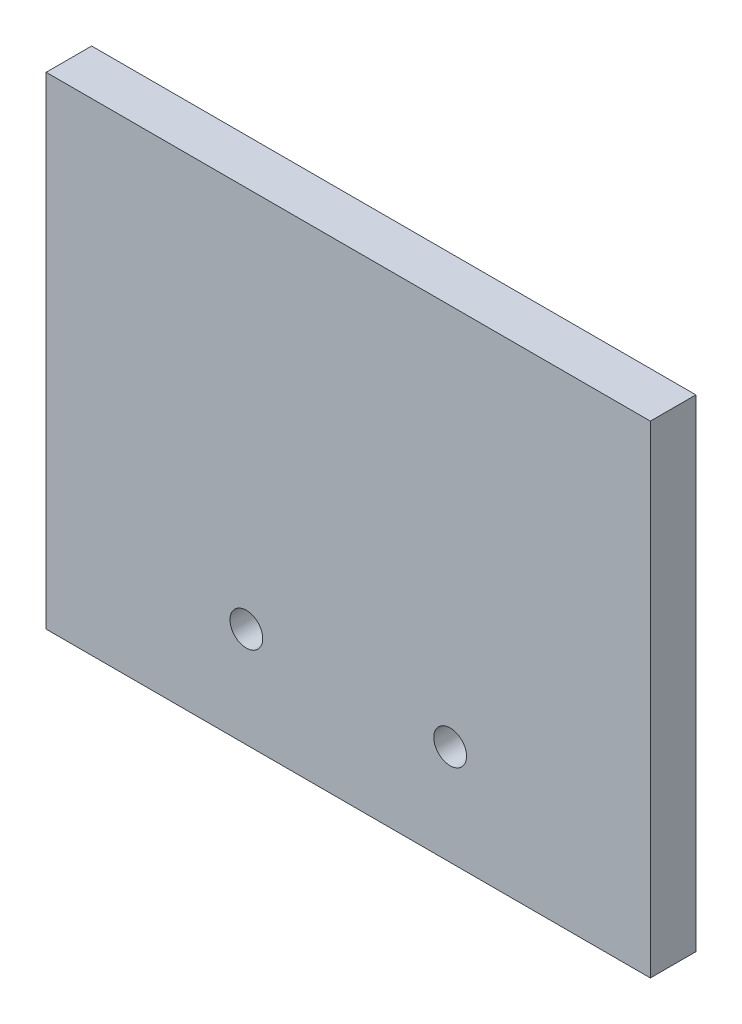
SolidWorks part; units mm, degrees
ref_plane "前视基准面" through (0, 0, 0) normal (0, 0, 1) x (1, 0, 0)
ref_plane "上视基准面" through (0, 0, 0) normal (0, 1, 0) x (1, 0, 0)
ref_plane "右视基准面" through (0, 0, 0) normal (1, 0, 0) x (0, 0, -1)
sketch "Sketch1" plane through (0, 0, 0) normal (0, 1, 0) x (1, 0, 0)
  line L1 (0, 0) -> (50, 0)
  line L2 (0, 0) -> (0, 9.1)
  line L3 (0, 9.1) -> (50, 9.1)
  line L4 (50, 0) -> (50, 9.1)
  dimension "D1" = 50
  dimension "D2" = 9.1
extrude "Boss-Extrude1" add sketch "Sketch1" along normal blind 2
sketch "Sketch2" plane through (0, 2, 0) normal (0, 1, 0) x (1, 0, 0)
  line L0 (50, 9.1) -> (0, 9.1) construction
  line L1 (12.5, 9.1) -> (37.5, 9.1)
  line L2 (12.5, 9.1) -> (12.5, 2.5)
  line L3 (12.5, 2.5) -> (37.5, 2.5)
  line L4 (37.5, 9.1) -> (37.5, 2.5)
  line L5 (0, 9.1) -> (0, 0) construction
  line L6 (50, 0) -> (50, 9.1) construction
  point P8 (50, 4.55)
  dimension "D1" = 6.6
  dimension "D2" = 12.5
  dimension "D3" = 12.5
extrude "Cut-Extrude1" cut sketch "Sketch2" against normal blind 2
sketch "Sketch3" plane through (0, 2, 0) normal (0, 1, 0) x (1, 0, 0)
  line L0 (12.5, 9.1) -> (0, 9.1) construction
  line L1 (50, 9.1) -> (37.5, 9.1) construction
  line L3 (37.5, 2.5) -> (37.5, 9.1) construction
  line L5 (0, 9.1) -> (0, 0) construction
  circle A0 centre (6.25, 5.8) radius 1.8
  circle A1 centre (43.75, 5.8) radius 1.8
  dimension "D1" = 3.6
  dimension "D2" = 3.6
  dimension "D4" = 3.3
  dimension "D3" = 3.3
  dimension "D5" = 6.25
  dimension "D6" = 6.25
extrude "Cut-Extrude2" cut sketch "Sketch3" against normal blind 2
sketch "Sketch4" plane through (0, 2, 0) normal (0, 1, 0) x (1, 0, 0)
  line L0 (0, 0) -> (50, 0) construction
  line L1 (-8.2, 0) -> (58.2, 0)
  line L2 (-8.2, 0) -> (-8.2, -130)
  line L3 (-8.2, -130) -> (58.2, -130)
  line L4 (58.2, 0) -> (58.2, -130)
  line L5 (12.5, 2.5) -> (37.5, 2.5) construction
  point P6 (25, 2.5)
  dimension "D1" = 130
  dimension "D2" = 0
  dimension "D3" = 33.2
  dimension "D4" = 66.4
extrude "Boss-Extrude2" add sketch "Sketch4" against normal blind 2
sketch "Sketch5" plane through (0, 0, 130) normal (0, 0, 1) x (1, 0, 0)
  line L1 (-8.2, 2) -> (58.2, 2)
  line L2 (-8.2, 2) -> (-8.2, 0)
  line L3 (-8.2, 0) -> (58.2, 0)
  line L4 (58.2, 2) -> (58.2, 0)
extrude "Boss-Extrude3" add sketch "Sketch5" along normal blind 2.5
sketch "Sketch6" plane through (0, 2, 0) normal (0, 1, 0) x (1, 0, 0)
  line L1 (-8.2, -132.5) -> (-16.8, -132.5)
  line L2 (-8.2, -132.5) -> (-8.2, -70)
  line L3 (-8.2, -70) -> (-16.8, -70)
  line L4 (-16.8, -132.5) -> (-16.8, -70)
  line L5 (58.2, -132.5) -> (66.8, -132.5)
  line L6 (58.2, -132.5) -> (58.2, -70)
  line L7 (58.2, -70) -> (66.8, -70)
  line L8 (66.8, -132.5) -> (66.8, -70)
  dimension "D1" = 8.6
  dimension "D2" = 8.6
  dimension "D3" = 62.5
  dimension "D4" = 62.5
extrude "Boss-Extrude4" add sketch "Sketch6" against normal blind 2
sketch "Sketch7" plane through (0, 2, 0) normal (0, 1, 0) x (1, 0, 0)
  line L0 (-13.5, -64.2883) -> (-13.5, -157.5169) construction
  line L1 (63.5, -64.2883) -> (63.5, -152.5529) construction
  line L2 (-16.8, -70) -> (-16.8, -132.5) construction
  line L3 (66.8, -132.5) -> (66.8, -70) construction
  line L4 (-8.2, -70) -> (-16.8, -70) construction
  line L5 (66.8, -132.5) -> (-16.8, -132.5) construction
  line L6 (66.8, -70) -> (58.2, -70) construction
  line L7 (-15, -115) -> (-12, -115)
  line L8 (-15, -115) -> (-15, -120)
  line L9 (-15, -120) -> (-12, -120)
  line L10 (-12, -115) -> (-12, -120)
  line L11 (62, -115) -> (65, -115)
  line L12 (62, -115) -> (62, -120)
  line L13 (62, -120) -> (65, -120)
  line L14 (65, -115) -> (65, -120)
  circle A0 centre (-13.5, -77) radius 1.8
  circle A1 centre (-13.5, -101.25) radius 1.8
  circle A2 centre (-13.5, -125.5) radius 1.8
  circle A3 centre (63.5, -77) radius 1.8
  circle A4 centre (63.5, -101.25) radius 1.8
  circle A5 centre (63.5, -125.5) radius 1.8
  dimension "D3" = 3.6
  dimension "D4" = 3.6
  dimension "D6" = 3.6
  dimension "D12" = 3.6
  dimension "D13" = 3.6
  dimension "D14" = 3.6
  dimension "D1" = 3.3
  dimension "D2" = 3.3
  dimension "D5" = 31.25
  dimension "D7" = 7
  dimension "D8" = 1.5
  dimension "D9" = 3
  dimension "D10" = 5
  dimension "D11" = 12.5
  dimension "D15" = 1.5
  dimension "D16" = 3
  dimension "D17" = 7
  dimension "D18" = 7
extrude "Cut-Extrude3" cut sketch "Sketch7" against normal blind 2
sketch "Sketch8" plane through (0, 2, 0) normal (0, 1, 0) x (1, 0, 0)
  line L0 (25, 2.5) -> (25, -143.8166) construction
  line L1 (12.5, 2.5) -> (37.5, 2.5) construction
  line L3 (12.5, 0) -> (37.5, 0)
  line L4 (12.5, 0) -> (12.5, -45)
  line L5 (12.5, -45) -> (37.5, -45)
  line L6 (37.5, 0) -> (37.5, -45)
  dimension "D1" = 25
  dimension "D2" = 12.5
  dimension "D3" = 45
extrude "Cut-Extrude4" cut sketch "Sketch8" against normal blind 20
sketch "Sketch9" plane through (0, 2, 0) normal (0, 1, 0) x (1, 0, 0)
  line L0 (37.5, -45) -> (37.5, 0) construction
  line L1 (12.5, 0) -> (37.5, 0)
  line L2 (12.5, 0) -> (12.5, -10)
  line L3 (12.5, -10) -> (37.5, -10)
  line L4 (37.5, 0) -> (37.5, -10)
  dimension "D1" = 10
extrude "Boss-Extrude5" add sketch "Sketch9" against normal blind 2
sketch "Sketch10" plane through (0, 2, 0) normal (0, 1, 0) x (1, 0, 0)
  line L0 (-8.2, 0) -> (-8.2, -70) construction
  line L1 (-8.2, -16) -> (-42.9, -16)
  line L2 (-8.2, -16) -> (-8.2, -43.07)
  line L3 (-8.2, -43.07) -> (-42.9, -43.07)
  line L4 (-42.9, -16) -> (-42.9, -43.07)
  line L5 (0, 0) -> (-8.2, 0) construction
  line L6 (58.2, -70) -> (58.2, 0) construction
  line L7 (58.2, -16) -> (92.9, -16)
  line L8 (58.2, -16) -> (58.2, -43.07)
  line L9 (58.2, -43.07) -> (92.9, -43.07)
  line L10 (92.9, -16) -> (92.9, -43.07)
  dimension "D1" = 16
  dimension "D2" = 27.07
  dimension "D3" = 34.7
  dimension "D4" = 34.7
extrude "Boss-Extrude6" add sketch "Sketch10" against normal blind 2
sketch "Sketch11" plane through (0, 2, 0) normal (0, 1, 0) x (1, 0, 0)
  line L0 (-48.2559, -39.82) -> (25.7485, -39.82) construction
  line L1 (-47.1851, -19.25) -> (20.7514, -19.25) construction
  line L2 (-8.2, -16) -> (-42.9, -16) construction
  line L3 (-42.9, -43.07) -> (-8.2, -43.07) construction
  line L4 (-42.9, -16) -> (-42.9, -43.07) construction
  circle A0 centre (-36.9, -19.25) radius 1.8
  circle A1 centre (-36.9, -39.82) radius 1.8
  circle A2 centre (-22.6, -19.25) radius 1.8
  circle A3 centre (-22.6, -39.82) radius 1.8
  dimension "D5" = 3.6
  dimension "D6" = 3.6
  dimension "D7" = 3.6
  dimension "D8" = 3.6
  dimension "D10" = 20.3
  dimension "D1" = 3.25
  dimension "D2" = 3.25
  dimension "D3" = 6
  dimension "D4" = 6
  dimension "D9" = 20.3
extrude "Cut-Extrude5" cut sketch "Sketch11" against normal blind 2
sketch "Sketch12" plane through (0, 2, 0) normal (0, 1, 0) x (1, 0, 0)
  line L0 (39.2942, -19.25) -> (115.8735, -19.25) construction
  line L1 (40.8036, -39.82) -> (109.9769, -39.82) construction
  line L2 (92.9, -43.07) -> (92.9, -16) construction
  circle A0 centre (72.6, -19.25) radius 1.8
  circle A1 centre (86.9, -19.25) radius 1.8
  circle A2 centre (72.6, -39.82) radius 1.8
  circle A3 centre (86.9, -39.82) radius 1.8
  dimension "D1" = 3.6
  dimension "D2" = 3.6
  dimension "D5" = 3.6
  dimension "D6" = 3.6
  dimension "D3" = 6
  dimension "D4" = 20.3
extrude "Cut-Extrude6" cut sketch "Sketch12" against normal blind 2
sketch "Sketch13" plane through (-42.9, 0, 0) normal (-1, 0, 0) x (0, 0, 1)
  line L1 (16, 2) -> (14, 2)
  line L2 (16, 2) -> (16, 0)
  line L3 (16, 0) -> (14, 0)
  line L4 (14, 2) -> (14, 0)
  line L5 (43.07, 2) -> (45.07, 2)
  line L6 (43.07, 2) -> (43.07, 0)
  line L7 (43.07, 0) -> (45.07, 0)
  line L8 (45.07, 2) -> (45.07, 0)
  dimension "D1" = 2
  dimension "D2" = 2
extrude "Boss-Extrude7" add sketch "Sketch13" against normal blind 44
sketch "Sketch14" plane through (92.9, 0, 0) normal (1, 0, 0) x (0, 0, -1)
  line L1 (-16, 2) -> (-14, 2)
  line L2 (-16, 2) -> (-16, 0)
  line L3 (-16, 0) -> (-14, 0)
  line L4 (-14, 2) -> (-14, 0)
  line L5 (-43.07, 0) -> (-45.07, 0)
  line L6 (-43.07, 0) -> (-43.07, 2)
  line L7 (-43.07, 2) -> (-45.07, 2)
  line L8 (-45.07, 0) -> (-45.07, 2)
  dimension "D1" = 2
  dimension "D2" = 2
extrude "Boss-Extrude8" add sketch "Sketch14" against normal blind 46
sketch "Sketch16" plane through (0, 2, 0) normal (0, 1, 0) x (1, 0, 0)
  line L0 (66.8, -132.5) -> (-16.8, -132.5) construction
  line L1 (4, -132.5) -> (46, -132.5)
  line L2 (4, -132.5) -> (4, -175.5)
  line L3 (4, -175.5) -> (46, -175.5)
  line L4 (46, -132.5) -> (46, -175.5)
  line L5 (37.5, -45) -> (12.5, -45) construction
  point P6 (25, -45)
  dimension "D1" = 42
  dimension "D2" = 43
  dimension "D3" = 21
extrude "Boss-Extrude10" add sketch "Sketch16" against normal blind 2
sketch "Sketch18" plane through (0, 2, 0) normal (0, 1, 0) x (1, 0, 0)
  line L0 (4, -175.5) -> (46, -175.5) construction
  line L1 (4, -132.5) -> (4, -175.5) construction
  line L2 (46, -175.5) -> (46, -132.5) construction
  line L3 (4, -132.5) -> (-16.8, -132.5) construction
  line L4 (66.8, -132.5) -> (46, -132.5) construction
  circle A0 centre (8.74, -171.03) radius 1.8
  circle A1 centre (41.26, -171.03) radius 1.8
  circle A2 centre (8.74, -138.5) radius 1.8
  circle A3 centre (41.26, -138.5) radius 1.8
  dimension "D3" = 3.6
  dimension "D6" = 3.6
  dimension "D7" = 3.6
  dimension "D8" = 3.6
  dimension "D1" = 4.47
  dimension "D2" = 4.74
  dimension "D4" = 4.47
  dimension "D5" = 4.74
  dimension "D9" = 6
  dimension "D10" = 6
extrude "Cut-Extrude7" cut sketch "Sketch18" against normal blind 2
sketch "Sketch20" plane through (0, 2, 0) normal (0, 1, 0) x (1, 0, 0)
  line L0 (-2, -132.5) -> (4, -132.5)
  line L1 (4, -132.5) -> (-16.8, -132.5) construction
  line L2 (4, -132.5) -> (4, -138.5)
  line L3 (4, -132.5) -> (4, -175.5) construction
  line L4 (46, -138.5) -> (46, -132.5)
  line L5 (46, -175.5) -> (46, -132.5) construction
  line L6 (46, -132.5) -> (52, -132.5)
  line L7 (66.8, -132.5) -> (46, -132.5) construction
  arc A0 (-2, -132.5) -> (4, -138.5) centre (-2, -138.5) cw
  arc A1 (52, -132.5) -> (46, -138.5) centre (52, -138.5) ccw
  dimension "D1" = 6
  dimension "D2" = 6
  dimension "D3" = 6
extrude "Boss-Extrude12" add sketch "Sketch20" against normal blind 2 contours L0 A0 L2 | A1 L6 L4
sketch "Sketch21" plane through (0, 0, -9.1) normal (0, 0, -1) x (-1, 0, 0)
  line L1 (-50, 2) -> (-52, 2)
  line L2 (-50, 2) -> (-50, 0)
  line L3 (-50, 0) -> (-52, 0)
  line L4 (-52, 2) -> (-52, 0)
  line L5 (-37.5, 2) -> (-35.5, 2)
  line L6 (-37.5, 2) -> (-37.5, 0)
  line L7 (-37.5, 0) -> (-35.5, 0)
  line L8 (-35.5, 2) -> (-35.5, 0)
  line L9 (-12.5, 2) -> (-14.5, 2)
  line L10 (-12.5, 2) -> (-12.5, 0)
  line L11 (-12.5, 0) -> (-14.5, 0)
  line L12 (-14.5, 2) -> (-14.5, 0)
  line L13 (0, 2) -> (2, 2)
  line L14 (0, 2) -> (0, 0)
  line L15 (0, 0) -> (2, 0)
  line L16 (2, 2) -> (2, 0)
  dimension "D1" = 2
  dimension "D2" = 2
  dimension "D3" = 2
  dimension "D4" = 2
extrude "Boss-Extrude13" add sketch "Sketch21" against normal blind 10
sketch "Sketch25" plane through (0, 2, 0) normal (0, 1, 0) x (1, 0, 0)
  line L0 (-11.7, -6.4239) -> (-11.7, -56.5762) construction
  line L1 (-8.2, 0) -> (-8.2, -14) construction
  line L2 (61.7, -6.4239) -> (61.7, -56.5762) construction
  line L3 (58.2, -14) -> (58.2, 0) construction
  line L4 (-8.2, -14) -> (-42.9, -14) construction
  line L5 (-13.2, -20) -> (-10.2, -20)
  line L6 (-13.2, -20) -> (-13.2, -25)
  line L7 (-13.2, -25) -> (-10.2, -25)
  line L8 (-10.2, -20) -> (-10.2, -25)
  line L9 (-8.2, -45.07) -> (-42.9, -45.07) construction
  line L10 (-13.2, -34.07) -> (-10.2, -34.07)
  line L11 (-13.2, -34.07) -> (-13.2, -39.07)
  line L12 (-13.2, -39.07) -> (-10.2, -39.07)
  line L13 (-10.2, -34.07) -> (-10.2, -39.07)
  line L14 (58.2, -14) -> (92.9, -14) construction
  line L15 (60.2, -20) -> (63.2, -20)
  line L16 (60.2, -20) -> (60.2, -25)
  line L17 (60.2, -25) -> (63.2, -25)
  line L18 (63.2, -20) -> (63.2, -25)
  line L19 (60.2, -34.07) -> (63.2, -34.07)
  line L20 (60.2, -34.07) -> (60.2, -39.07)
  line L21 (60.2, -39.07) -> (63.2, -39.07)
  line L22 (63.2, -34.07) -> (63.2, -39.07)
  line L23 (58.2, -45.07) -> (92.9, -45.07) construction
  dimension "D1" = 3.5
  dimension "D2" = 3.5
  dimension "D3" = 3
  dimension "D4" = 1.5
  dimension "D5" = 5
  dimension "D6" = 6
  dimension "D7" = 5
  dimension "D8" = 6
  dimension "D9" = 3
  dimension "D10" = 1.5
  dimension "D11" = 1.5
  dimension "D12" = 3
  dimension "D13" = 1.5
  dimension "D14" = 3
  dimension "D15" = 6
  dimension "D16" = 6
extrude "Cut-Extrude8" cut sketch "Sketch25" against normal blind 10
sketch "Sketch26" plane through (0, 2, 0) normal (0, 1, 0) x (1, 0, 0)
  line L1 (-2, 0) -> (-8.2, 0)
  line L2 (-2, 0) -> (-2, 13)
  line L3 (-2, 13) -> (-8.2, 13)
  line L4 (-8.2, 0) -> (-8.2, 13)
  line L5 (58.2, 0) -> (52, 0)
  line L6 (58.2, 0) -> (58.2, 13)
  line L7 (58.2, 13) -> (52, 13)
  line L8 (52, 0) -> (52, 13)
  line L9 (-2, 13) -> (52, 13)
  line L10 (-2, 13) -> (-2, 9.1)
  line L11 (-2, 9.1) -> (52, 9.1)
  line L12 (52, 13) -> (52, 9.1)
  line L13 (35.5, 2.5) -> (14.5, 2.5)
  line L14 (35.5, 2.5) -> (35.5, 9.1)
  line L15 (35.5, 9.1) -> (14.5, 9.1)
  line L16 (14.5, 2.5) -> (14.5, 9.1)
  dimension "D1" = 13
extrude "Boss-Extrude14" add sketch "Sketch26" against normal blind 2 contours L4 L1 L2 L3 | L2 L11 L8 L9 | L16 L13 L14 L11 | L8 L5 L6 L7
sketch "Sketch27" plane through (0, 2, 0) normal (0, 1, 0) x (1, 0, 0)
  line L0 (-8.2, -14) -> (-42.9, -14) construction
  line L1 (-8.2, 13) -> (-10.2, 13)
  line L2 (-8.2, 13) -> (-8.2, -14)
  line L3 (-8.2, -14) -> (-10.2, -14)
  line L4 (-10.2, 13) -> (-10.2, -14)
  line L5 (-8.2, -45.07) -> (-42.9, -45.07) construction
  line L6 (-10.2, -45.07) -> (-8.2, -45.07)
  line L7 (-10.2, -45.07) -> (-10.2, -70)
  line L8 (-10.2, -70) -> (-8.2, -70)
  line L9 (-8.2, -45.07) -> (-8.2, -70)
  line L10 (58.2, -14) -> (92.9, -14) construction
  line L11 (58.2, 13) -> (60.2, 13)
  line L12 (58.2, 13) -> (58.2, -14)
  line L13 (58.2, -14) -> (60.2, -14)
  line L14 (60.2, 13) -> (60.2, -14)
  line L15 (66.8, -70) -> (58.2, -70) construction
  line L16 (58.2, -45.07) -> (60.2, -45.07)
  line L17 (58.2, -45.07) -> (58.2, -70)
  line L18 (58.2, -70) -> (60.2, -70)
  line L19 (60.2, -45.07) -> (60.2, -70)
extrude "Boss-Extrude15" add sketch "Sketch27" against normal blind 2
sketch "Sketch29" plane through (0, 2, 0) normal (0, 1, 0) x (1, 0, 0)
  line L1 (-10.2, -14) -> (-20.2, -14)
  line L2 (-10.2, -14) -> (-10.2, -4)
  line L3 (-10.2, -4) -> (-20.2, -4)
  line L4 (-20.2, -14) -> (-20.2, -4)
  line L5 (-10.2, -45.07) -> (-20.2, -45.07)
  line L6 (-10.2, -45.07) -> (-10.2, -55.07)
  line L7 (-10.2, -55.07) -> (-20.2, -55.07)
  line L8 (-20.2, -45.07) -> (-20.2, -55.07)
  line L9 (60.2, -14) -> (70.2, -14)
  line L10 (60.2, -14) -> (60.2, -4)
  line L11 (60.2, -4) -> (70.2, -4)
  line L12 (70.2, -14) -> (70.2, -4)
  line L13 (60.2, -45.07) -> (70.2, -45.07)
  line L14 (60.2, -45.07) -> (60.2, -55.07)
  line L15 (60.2, -55.07) -> (70.2, -55.07)
  line L16 (70.2, -45.07) -> (70.2, -55.07)
  dimension "D1" = 10
  dimension "D2" = 10
  dimension "D3" = 10
  dimension "D4" = 10
  dimension "D5" = 10
  dimension "D6" = 10
  dimension "D7" = 10
extrude "Boss-Extrude19" add sketch "Sketch29" against normal blind 2
sketch "Sketch41" plane through (0, 2, 0) normal (0, 1, 0) x (1, 0, 0)
  circle A0 centre (-15.2, -9) radius 1.8
  circle A1 centre (-15.2, -50.07) radius 1.8
  circle A2 centre (65.2, -9) radius 1.8
  circle A3 centre (65.2, -50.07) radius 1.8
  dimension "D1" = 3.6
  dimension "D2" = 3.6
  dimension "D3" = 3.6
  dimension "D4" = 3.6
extrude "Cut-Extrude15" cut sketch "Sketch41" against normal blind 2
sketch "Sketch42" plane through (0, 2, 0) normal (0, 1, 0) x (1, 0, 0)
  line L0 (60.2, -70) -> (60.2, -55.07) construction
  line L1 (-10.2, -70) -> (-16.8, -70) construction
  line L2 (-16.8, -70) -> (-10.2, -70)
  line L3 (-10.2, -70) -> (-10.2, -63.4)
  line L4 (60.2, -63.4) -> (60.2, -70)
  line L5 (60.2, -70) -> (66.8, -70)
  arc A0 (-16.8, -70) -> (-10.2, -63.4) centre (-16.8, -63.4) ccw
  arc A1 (66.8, -70) -> (60.2, -63.4) centre (66.8, -63.4) cw
  dimension "D1" = 6.6
extrude "Boss-Extrude26" add sketch "Sketch42" against normal blind 2
sketch "Sketch43" plane through (0, 0, -13) normal (0, 0, -1) x (-1, 0, 0)
  line L1 (10.2, 2) -> (-60.2, 2)
  line L2 (10.2, 2) -> (10.2, 0)
  line L3 (10.2, 0) -> (-60.2, 0)
  line L4 (-60.2, 2) -> (-60.2, 0)
extrude "Boss-Extrude27" add sketch "Sketch43" along normal blind 11
sketch "Sketch44" plane through (0, 2, 0) normal (0, 1, 0) x (1, 0, 0)
  line L0 (-10.2, -55.07) -> (-10.2, -63.4) construction
  line L1 (-20.2, -55.07) -> (-10.2, -55.07)
  line L2 (-20.2, -55.07) -> (-20.2, -60.07)
  line L3 (-20.2, -60.07) -> (-10.2, -60.07)
  line L4 (-10.2, -55.07) -> (-10.2, -60.07)
  line L5 (60.2, -63.4) -> (60.2, -55.07) construction
  line L6 (70.2, -55.07) -> (60.2, -55.07)
  line L7 (70.2, -55.07) -> (70.2, -60.07)
  line L8 (70.2, -60.07) -> (60.2, -60.07)
  line L9 (60.2, -55.07) -> (60.2, -60.07)
  dimension "D1" = 5
extrude "Boss-Extrude28" add sketch "Sketch44" against normal blind 2
sketch "Sketch45" plane through (0, 2, 0) normal (0, 1, 0) x (1, 0, 0)
  circle A0 centre (-15.2, -50.07) radius 1.8
  circle A1 centre (65.2, -50.07) radius 1.8
extrude "Boss-Extrude29" add sketch "Sketch45" against normal blind 2
sketch "Sketch46" plane through (0, 2, 0) normal (0, 1, 0) x (1, 0, 0)
  line L0 (-20.2, -60.07) -> (-10.2, -60.07) construction
  line L1 (60.2, -60.07) -> (70.2, -60.07) construction
  line L2 (-20.2, -45.07) -> (-20.2, -60.07) construction
  line L3 (70.2, -60.07) -> (70.2, -45.07) construction
  circle A0 centre (-15.2, -55.07) radius 1.8
  circle A1 centre (65.2, -55.07) radius 1.8
  dimension "D2" = 3.6
  dimension "D3" = 3.6
  dimension "D1" = 5
  dimension "D4" = 5
  dimension "D5" = 5
  dimension "D6" = 5
extrude "Cut-Extrude16" cut sketch "Sketch46" against normal blind 2
sketch "Sketch47" plane through (0, 2, 0) normal (0, 1, 0) x (1, 0, 0)
  line L0 (-10.2, 24) -> (-10.2, -4) construction
  line L1 (-20.2, -4) -> (-10.2, -4)
  line L2 (-20.2, -4) -> (-20.2, -3)
  line L3 (-20.2, -3) -> (-10.2, -3)
  line L4 (-10.2, -4) -> (-10.2, -3)
  line L5 (-10.2, -60.07) -> (-10.2, -63.4) construction
  line L6 (-20.2, -60.07) -> (-10.2, -60.07)
  line L7 (-20.2, -60.07) -> (-20.2, -61.07)
  line L8 (-20.2, -61.07) -> (-10.2, -61.07)
  line L9 (-10.2, -60.07) -> (-10.2, -61.07)
  line L10 (60.2, -63.4) -> (60.2, -60.07) construction
  line L11 (60.2, -4) -> (70.2, -4)
  line L12 (60.2, -4) -> (60.2, -3)
  line L13 (60.2, -3) -> (70.2, -3)
  line L14 (70.2, -4) -> (70.2, -3)
  line L15 (70.2, -60.07) -> (60.2, -60.07)
  line L16 (70.2, -60.07) -> (70.2, -61.07)
  line L17 (70.2, -61.07) -> (60.2, -61.07)
  line L18 (60.2, -60.07) -> (60.2, -61.07)
  dimension "D1" = 1
  dimension "D2" = 1
extrude "Boss-Extrude30" add sketch "Sketch47" against normal blind 2
sketch "Sketch48" plane through (0, 2, 0) normal (0, 1, 0) x (1, 0, 0)
  line L1 (-42.9, -14) -> (-10.2, -14)
  line L2 (-42.9, -14) -> (-42.9, -45.07)
  line L3 (-42.9, -45.07) -> (-10.2, -45.07)
  line L4 (-10.2, -14) -> (-10.2, -45.07)
  line L5 (92.9, -14) -> (60.2, -14)
  line L6 (92.9, -14) -> (92.9, -45.07)
  line L7 (92.9, -45.07) -> (60.2, -45.07)
  line L8 (60.2, -14) -> (60.2, -45.07)
  line L9 (-20.2, -61.07) -> (81.55, -61.07)
  line L10 (-20.2, -61.07) -> (-20.2, -181.5574)
  line L11 (-20.2, -181.5574) -> (81.55, -181.5574)
  line L12 (81.55, -61.07) -> (81.55, -181.5574)
extrude "Cut-Extrude17" cut sketch "Sketch48" against normal blind 20
sketch "Sketch50" plane through (0, 2, 0) normal (0, 1, 0) x (1, 0, 0)
  line L0 (-10.2, 24) -> (-10.2, -3) construction
  line L1 (-8.2, 22) -> (58.2, 22)
  line L2 (-8.2, 22) -> (-8.2, -59.07)
  line L3 (-8.2, -59.07) -> (58.2, -59.07)
  line L4 (58.2, 22) -> (58.2, -59.07)
  line L5 (-10.2, 24) -> (60.2, 24) construction
  line L6 (-20.2, -61.07) -> (70.2, -61.07) construction
  line L7 (60.2, -3) -> (60.2, 24) construction
  dimension "D1" = 2
  dimension "D2" = 2
  dimension "D3" = 2
  dimension "D4" = 2
extrude "Cut-Extrude19" cut sketch "Sketch50" against normal blind 20
sketch "Sketch51" plane through (0, 2, 0) normal (0, 1, 0) x (1, 0, 0)
  line L0 (-20.2, -61.07) -> (70.2, -61.07) construction
  line L1 (-10.2, 24) -> (60.2, 24)
  line L2 (-10.2, 24) -> (-10.2, -61.07)
  line L3 (-10.2, -61.07) -> (60.2, -61.07)
  line L4 (60.2, 24) -> (60.2, -61.07)
  line L6 (58.2, -59.07) -> (-8.2, -59.07)
  line L7 (58.2, -59.07) -> (58.2, 22)
  line L8 (58.2, 22) -> (-8.2, 22)
  line L9 (-8.2, -59.07) -> (-8.2, 22)
extrude "Boss-Extrude31" add sketch "Sketch51" along normal blind 20
sketch "Sketch52" plane through (0, 2, 0) normal (0, 1, 0) x (1, 0, 0)
  line L0 (-10.2, 24) -> (-10.2, -61.07) construction
  line L1 (-20.2, -14) -> (-10.2, -14)
  line L2 (-20.2, -14) -> (-20.2, -15)
  line L3 (-20.2, -15) -> (-10.2, -15)
  line L4 (-10.2, -14) -> (-10.2, -15)
  line L5 (60.2, -61.07) -> (60.2, 24) construction
  line L6 (70.2, -14) -> (60.2, -14)
  line L7 (70.2, -14) -> (70.2, -15)
  line L8 (70.2, -15) -> (60.2, -15)
  line L9 (60.2, -14) -> (60.2, -15)
  dimension "D1" = 1
extrude "Boss-Extrude32" add sketch "Sketch52" against normal blind 2
sketch "Sketch53" plane through (0, 2, 0) normal (0, 1, 0) x (1, 0, 0)
  line L0 (-10.2, 24) -> (-10.2, -61.07) construction
  line L1 (-20.2, -45.07) -> (-10.2, -45.07)
  line L2 (-20.2, -45.07) -> (-20.2, -49.07)
  line L3 (-20.2, -49.07) -> (-10.2, -49.07)
  line L4 (-10.2, -45.07) -> (-10.2, -49.07)
  line L5 (60.2, -61.07) -> (60.2, 24) construction
  line L6 (70.2, -45.07) -> (60.2, -45.07)
  line L7 (70.2, -45.07) -> (70.2, -49.07)
  line L8 (70.2, -49.07) -> (60.2, -49.07)
  line L9 (60.2, -45.07) -> (60.2, -49.07)
  dimension "D1" = 4
  dimension "D2" = 4
extrude "Cut-Extrude20" cut sketch "Sketch53" against normal blind 2
sketch "Sketch54" plane through (0, 2, 0) normal (0, 1, 0) x (1, 0, 0)
  line L1 (-20.2, -3) -> (-10.2, -3)
  line L2 (-20.2, -3) -> (-20.2, -15)
  line L3 (-20.2, -15) -> (-10.2, -15)
  line L4 (-10.2, -3) -> (-10.2, -15)
  line L5 (-20.2, -49.07) -> (-10.2, -49.07)
  line L6 (-20.2, -49.07) -> (-20.2, -61.07)
  line L7 (-20.2, -61.07) -> (-10.2, -61.07)
  line L8 (-10.2, -49.07) -> (-10.2, -61.07)
  line L9 (60.2, -3) -> (70.2, -3)
  line L10 (60.2, -3) -> (60.2, -15)
  line L11 (60.2, -15) -> (70.2, -15)
  line L12 (70.2, -3) -> (70.2, -15)
  line L13 (60.2, -49.07) -> (70.2, -49.07)
  line L14 (60.2, -49.07) -> (60.2, -61.07)
  line L15 (60.2, -61.07) -> (70.2, -61.07)
  line L16 (70.2, -49.07) -> (70.2, -61.07)
  circle A0 centre (-15.2, -9) radius 1.8
  circle A1 centre (-15.2, -55.07) radius 1.8
  circle A2 centre (65.2, -9) radius 1.8
  circle A3 centre (65.2, -55.07) radius 1.8
extrude "Boss-Extrude33" add sketch "Sketch54" along normal blind 1
sketch "Sketch55" plane through (0, 0, 3) normal (0, 0, -1) x (-1, 0, 0)
  line L0 (20.2, 3) -> (10.2, 22)
  line L1 (10.2, 22) -> (10.2, 3)
  line L2 (10.2, 3) -> (20.2, 3)
  line L3 (-70.2, 3) -> (-60.2, 3)
  line L4 (-60.2, 3) -> (-60.2, 22)
  line L5 (-60.2, 22) -> (-70.2, 3)
sketch "Sketch56" plane through (0, 0, 15) normal (0, 0, 1) x (1, 0, 0)
  line L0 (-20.2, 3) -> (-10.2, 3)
  line L1 (-10.2, 3) -> (-10.2, 22)
  line L2 (-10.2, 22) -> (-20.2, 3)
  line L3 (70.2, 3) -> (60.2, 3)
  line L4 (60.2, 3) -> (60.2, 22)
  line L5 (60.2, 22) -> (70.2, 3)
sketch "Sketch57" plane through (0, 0, 49.07) normal (0, 0, -1) x (-1, 0, 0)
  line L0 (20.2, 3) -> (10.2, 3)
  line L1 (10.2, 22) -> (20.2, 3)
  line L2 (-70.2, 3) -> (-60.2, 3)
  line L3 (-60.2, 3) -> (-60.2, 22)
  line L4 (-60.2, 22) -> (-70.2, 3)
  line L5 (10.2, 3) -> (10.2, 22)
sketch "Sketch59" plane through (0, 0, -22) normal (0, 0, 1) x (1, 0, 0)
  line L0 (-8.2, 11) -> (58.2, 11) construction
  line L1 (-8.2, 0) -> (-8.2, 22) construction
  line L2 (58.2, 0) -> (58.2, 22) construction
  circle A0 centre (-3.2, 11) radius 1.8
  circle A1 centre (53.2, 11) radius 1.8
  circle A2 centre (25, 11) radius 1.8
  dimension "D1" = 3.6
  dimension "D2" = 3.6
  dimension "D5" = 3.6
  dimension "D3" = 5
  dimension "D4" = 5
extrude "Cut-Extrude23" cut sketch "Sketch59" against normal blind 16 and the other way blind 96
sketch "Sketch62" plane through (0, 0, 61.07) normal (0, 0, 1) x (1, 0, 0)
  line L1 (-8.5777, 16.369) -> (58.4073, 16.369)
  line L2 (-8.5777, 16.369) -> (-8.5777, 5.1196)
  line L3 (-8.5777, 5.1196) -> (58.4073, 5.1196)
  line L4 (58.4073, 16.369) -> (58.4073, 5.1196)
extrude "Boss-Extrude38" add sketch "Sketch62" against normal blind 1
sketch "Sketch65" plane through (0, 0, 59.07) normal (0, 0, -1) x (-1, 0, 0)
  line L0 (8.2, 11) -> (-58.2, 11) construction
  line L1 (8.2, 0) -> (8.2, 22) construction
  line L2 (-58.2, 0) -> (-58.2, 22) construction
  circle A0 centre (-13.8, 11) radius 1.8
  circle A1 centre (-36.2, 11) radius 1.8
  dimension "D2" = 3.6
  dimension "D4" = 3.6
  dimension "D1" = 22
  dimension "D3" = 22
extrude "Cut-Extrude27" cut sketch "Sketch65" against normal blind 3
sketch "Sketch66" plane through (-10.2, 0, 0) normal (-1, 0, 0) x (0, 0, 1)
  line L0 (-24, 22) -> (61.07, 22) construction
  circle A0 centre (32.035, 16) radius 1
  dimension "D1" = 6
  dimension "D2" = 2
extrude "Cut-Extrude28" cut sketch "Sketch66" against normal blind 87
extrude "Boss-Extrude41" add sketch "Sketch55" against normal blind 2
extrude "Boss-Extrude42" add sketch "Sketch56" against normal blind 2
extrude "Boss-Extrude43" add sketch "Sketch57" against normal blind 2
sketch "Sketch68" plane through (0, 0, 59.07) normal (0, 0, -1) x (-1, 0, 0)
  line L1 (-0.8965, 6.2744) -> (5.8953, 6.2744)
  line L2 (-0.8965, 6.2744) -> (-0.8965, 14.4185)
  line L3 (-0.8965, 14.4185) -> (5.8953, 14.4185)
  line L4 (5.8953, 6.2744) -> (5.8953, 14.4185)
  line L5 (-21.8815, 6.2744) -> (-27.3672, 6.2744)
  line L6 (-21.8815, 6.2744) -> (-21.8815, 14.4185)
  line L7 (-21.8815, 14.4185) -> (-27.3672, 14.4185)
  line L8 (-27.3672, 6.2744) -> (-27.3672, 14.4185)
  line L9 (-48.3497, 6.2744) -> (-56.1137, 6.2744)
  line L10 (-48.3497, 6.2744) -> (-48.3497, 17.9033)
  line L11 (-48.3497, 17.9033) -> (-56.1137, 17.9033)
  line L12 (-56.1137, 6.2744) -> (-56.1137, 17.9033)
extrude "Boss-Extrude44" add sketch "Sketch68" against normal blind 2
sketch "Sketch69" plane through (0, 0, 61.07) normal (0, 0, 1) x (1, 0, 0)
  line L0 (-20.2, 3) -> (-10.2, 3)
  line L1 (-10.2, 3) -> (-10.2, 22)
  line L2 (-10.2, 22) -> (-20.2, 3)
  line L3 (60.2, 3) -> (70.2, 3)
  line L4 (70.2, 3) -> (60.2, 22)
  line L5 (60.2, 22) -> (60.2, 3)
extrude "Boss-Extrude45" add sketch "Sketch69" against normal blind 2
sketch "Sketch70" plane through (-10.2, 0, 0) normal (-1, 0, 0) x (0, 0, 1)
  line L0 (5, 22) -> (13, 22) construction
  circle A0 centre (9, 17) radius 1.8
  circle A1 centre (55.07, 17) radius 1.8
  dimension "D1" = 3.6
  dimension "D3" = 3.6
  dimension "D2" = 5
extrude "Cut-Extrude29" cut sketch "Sketch70" against normal blind 83
sketch "Sketch72" plane through (0, 0, 59.07) normal (0, 0, -1) x (-1, 0, 0)
  line L1 (33.7821, 22) -> (-75.9121, 22)
  line L2 (33.7821, 22) -> (33.7821, -27.1241)
  line L3 (33.7821, -27.1241) -> (-75.9121, -27.1241)
  line L4 (-75.9121, 22) -> (-75.9121, -27.1241)
extrude "Cut-Extrude30" cut sketch "Sketch72" along normal blind 90
sketch "Sketch73" plane through (0, 0, 59.07) normal (0, 0, -1) x (-1, 0, 0)
  line L0 (10.2, 22) -> (-60.2, 22) construction
  line L1 (8.2, 22) -> (25.1065, 22)
  line L2 (8.2, 22) -> (8.2, -16.8253)
  line L3 (8.2, -16.8253) -> (25.1065, -16.8253)
  line L4 (25.1065, 22) -> (25.1065, -16.8253)
  line L6 (-58.2, 22) -> (-72.0565, 22)
  line L7 (-58.2, 22) -> (-58.2, -13.444)
  line L8 (-58.2, -13.444) -> (-72.0565, -13.444)
  line L9 (-72.0565, 22) -> (-72.0565, -13.444)
  dimension "D1" = 2
  dimension "D2" = 2
extrude "Cut-Extrude31" cut sketch "Sketch73" against normal blind 90
sketch "Sketch74" plane through (0, 22, 0) normal (0, 1, 0) x (1, 0, 0)
  line L1 (-8.2, -59.07) -> (58.2, -59.07)
  line L2 (-8.2, -59.07) -> (-8.2, -61.07)
  line L3 (-8.2, -61.07) -> (58.2, -61.07)
  line L4 (58.2, -59.07) -> (58.2, -61.07)
extrude "Boss-Extrude46" add sketch "Sketch74" along normal blind 31
sketch "Sketch75" plane through (0, 0, 59.07) normal (0, 0, -1) x (-1, 0, 0)
  line L1 (8.2, 0) -> (-58.2, 0)
  line L2 (8.2, 0) -> (8.2, 53)
  line L3 (8.2, 53) -> (-58.2, 53)
  line L4 (-58.2, 0) -> (-58.2, 53)
  circle A0 centre (-13.8, 11) radius 1.8
  circle A1 centre (-36.2, 11) radius 1.8
extrude "Boss-Extrude47" add sketch "Sketch75" along normal blind 3
